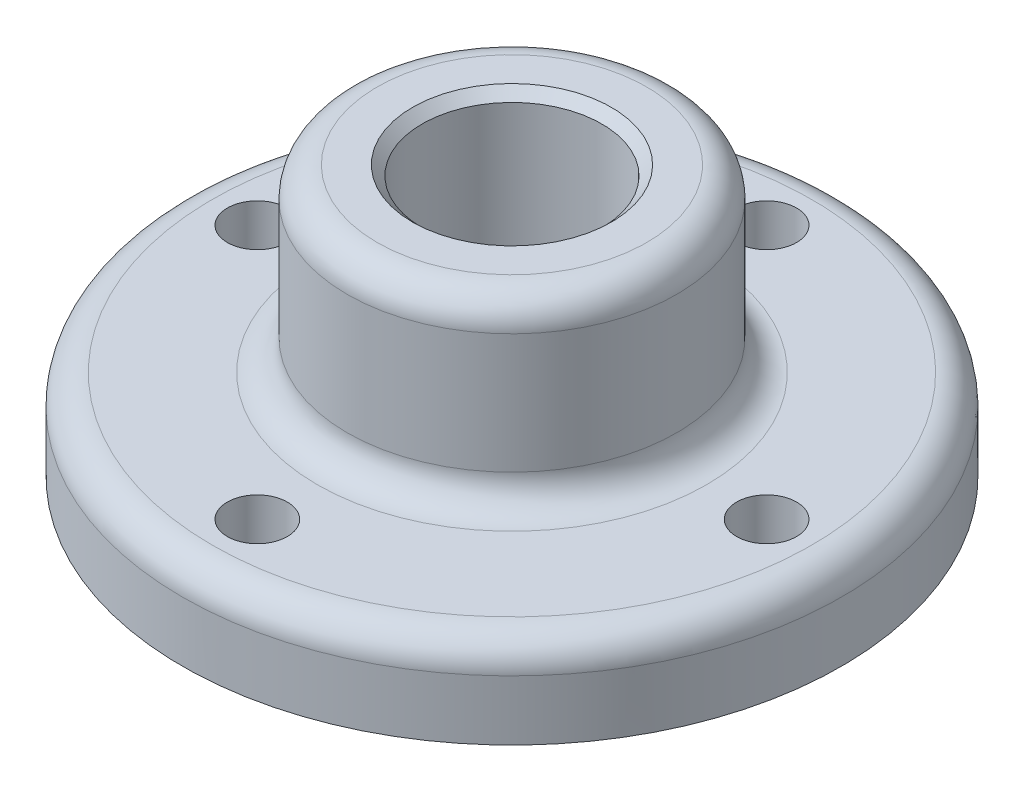
SolidWorks part; units mm, degrees
ref_plane "Front Plane" through (0, 0, 0) normal (0, 0, 1) x (1, 0, 0)
ref_plane "Top Plane" through (0, 0, 0) normal (0, 1, 0) x (1, 0, 0)
ref_plane "Right Plane" through (0, 0, 0) normal (1, 0, 0) x (0, 0, -1)
sketch "Sketch1" plane through (0, 0, 0) normal (0, 0, 1) x (1, 0, 0)
  line L0 (0, 0) -> (0, 50000) construction
  line L1 (0, 0) -> (69.85, 0)
  line L2 (69.85, 0) -> (69.85, 19.05)
  line L3 (69.85, 19.05) -> (34.925, 19.05)
  line L4 (34.925, 19.05) -> (34.925, 57.15)
  line L5 (34.925, 57.15) -> (0, 57.15)
  line L6 (0, 0) -> (0, 57.15)
  dimension "D1" = 139.7
  dimension "D2" = 57.15
  dimension "D3" = 19.05
  dimension "D4" = 69.85
revolve "Revolve1" add sketch "Sketch1" angle 360 about L0
sketch "Sketch2" plane through (0, 57.15, 0) normal (0, 1, 0) x (1, 0, 0)
  circle A0 centre (0, 0) radius 19.05
  circle A1 centre (0, 0) radius 34.925 construction
  circle A2 centre (0, 0) radius 34.925 construction
  dimension "D1" = 38.1
extrude "Cut-Extrude1" cut sketch "Sketch2" against normal through all
sketch "Sketch3" plane through (0, 19.05, 0) normal (0, 1, 0) x (1, 0, 0)
  line L0 (0, 0) -> (0, 53.975) construction
  circle A0 centre (0, 53.975) radius 6.35
  circle A1 centre (53.975, 0) radius 6.35
  circle A2 centre (0, -53.975) radius 6.35
  circle A3 centre (-53.975, 0) radius 6.35
  point P13 (0, 0)
  dimension "D2" = 12.7
  dimension "D1" = 53.975
  dimension "D3" = 4
extrude "Cut-Extrude2" cut sketch "Sketch3" against normal up to surface (19.05 mm away) up to face at (0, 0, 19.05)
fillet "Fillet1" radius 6.35 3 edges at (0, 19.05, -69.85) (0, 57.15, -34.925) (0, 19.05, -34.925)
chamfer "Chamfer1" distance 2.032 angle 45 1 edges at (0, 57.15, 19.05)
